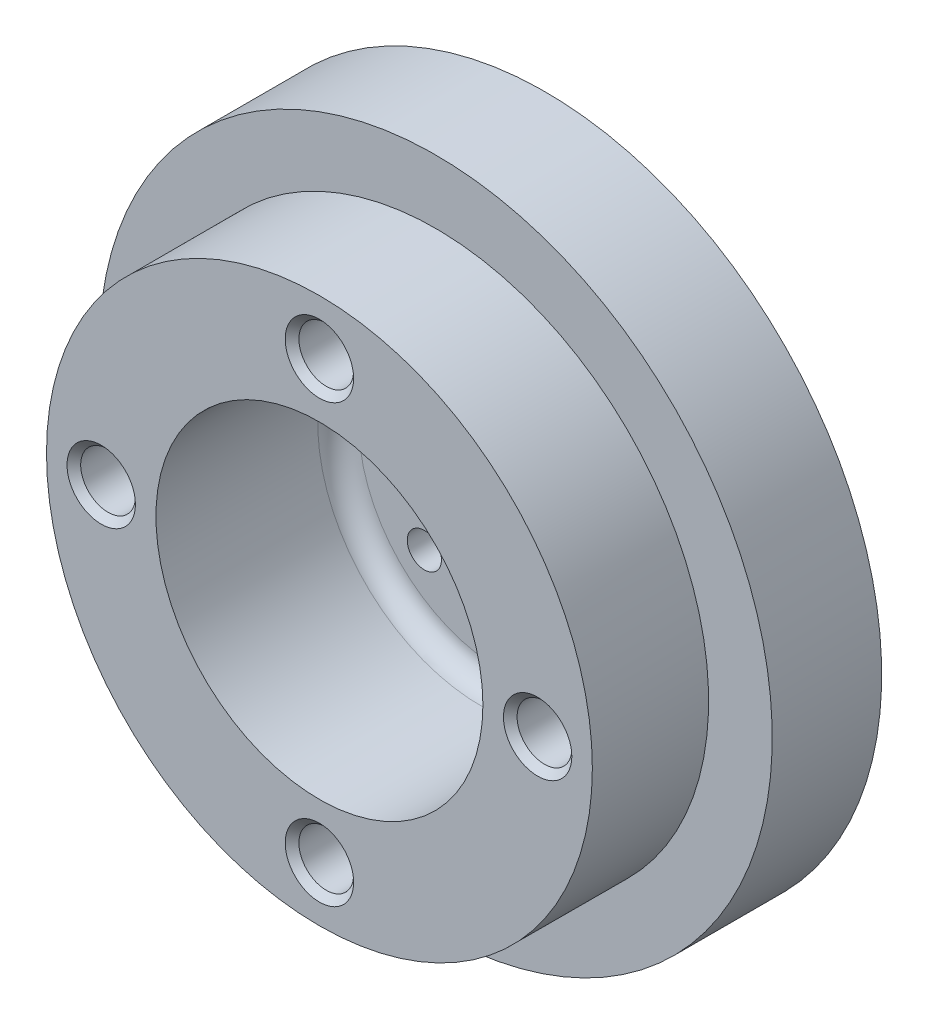
SolidWorks part; units mm, degrees
ref_plane "Front Plane" through (0, 0, 0) normal (0, 0, 1) x (1, 0, 0)
ref_plane "Top Plane" through (0, 0, 0) normal (0, 1, 0) x (1, 0, 0)
ref_plane "Right Plane" through (0, 0, 0) normal (1, 0, 0) x (0, 0, -1)
sketch "Sketch1" plane through (0, 0, 0) normal (0, 0, 1) x (1, 0, 0)
  circle A2 centre (0, 12) radius 4.2
  circle A3 centre (0, 12) radius 4.2
  circle A5 centre (0, 12) radius 19.75
  circle A6 centre (0, 12) radius 19.75
  circle A11 centre (5.6569, 17.6569) radius 1.25
  circle A12 centre (5.6569, 17.6569) radius 1.25
  circle A49 centre (8, 12) radius 1.25
  circle A50 centre (8, 12) radius 1.25
  circle A52 centre (5.6569, 6.3431) radius 1.25
  circle A53 centre (5.6569, 6.3431) radius 1.25
  circle A55 centre (0, 4) radius 1.25
  circle A56 centre (0, 4) radius 1.25
  circle A58 centre (-5.6569, 6.3431) radius 1.25
  circle A59 centre (-5.6569, 6.3431) radius 1.25
  circle A61 centre (-8, 12) radius 1.25
  circle A62 centre (-8, 12) radius 1.25
  circle A64 centre (-5.6569, 17.6569) radius 1.25
  circle A65 centre (-5.6569, 17.6569) radius 1.25
  circle A67 centre (0, 20) radius 1.25
  circle A68 centre (0, 20) radius 1.25
  dimension "D1" = 0.2
  dimension "D2" = 0.25
  dimension "D3" = 0.5
  dimension "D4" = 0.5
  dimension "D5" = 0.5
  dimension "D6" = 0.5
  dimension "D7" = 0.5
  dimension "D8" = 0.5
  dimension "D9" = 0.5
  dimension "D10" = 0.5
extrude "Boss-Extrude1" add sketch "Sketch1" along normal blind 3.175
sketch "Sketch3" plane through (0, 0, 3.175) normal (0, 0, 1) x (1, 0, 0)
  circle A1 centre (0, 12) radius 19.95
  circle A2 centre (0, 12) radius 11.95
  dimension "D2" = 39.9
  dimension "D1" = 8
extrude "Boss-Extrude2" add sketch "Sketch3" along normal offset from surface (13.325 mm away) 0.5
sketch "Sketch4" plane through (0, 0, 16.5) normal (0, 0, 1) x (1, 0, 0)
  line L0 (-19.95, 12) -> (-11.95, 12) construction
  circle A0 centre (-15.95, 12) radius 2
  circle A1 centre (0, 12) radius 19.95 construction
  circle A2 centre (0, 12) radius 11.95 construction
  point P9 (-15.95, 12)
  dimension "D1" = 4
extrude "Cut-Extrude1" cut sketch "Sketch4" against normal through all
pattern_circular "CirPattern1" count 4 over 360 about axis through (0, 12, 0) along (0, 0, 1) of "Cut-Extrude1"
sketch "Sketch5" plane through (0, 0, 0) normal (0, 0, -1) x (-1, 0, 0)
  circle A0 centre (0, 12) radius 19.75 construction
  circle A1 centre (0, 12) radius 19.75
  circle A2 centre (0, 12) radius 24.6 construction
  circle A3 centre (0, 12) radius 24.6
extrude "Boss-Extrude3" add sketch "Sketch5" against normal up to surface (8 mm away)
chamfer "Chamfer1" distance 0.5 angle 45 4 edges at (13.95, 12, 16.5) (0, 25.95, 16.5) (0, -1.95, 16.5) (-13.95, 12, 16.5)
fillet "Fillet1" radius 1.5 1 edges at (11.95, 12, 3.175)
equation "\"D9@Sketch1\"=\"D10@Sketch1\""
equation "\"D8@Sketch1\"=\"D10@Sketch1\""
equation "\"D7@Sketch1\"=\"D10@Sketch1\""
equation "\"D6@Sketch1\"=\"D10@Sketch1\""
equation "\"D5@Sketch1\"=\"D10@Sketch1\""
equation "\"D4@Sketch1\"=\"D10@Sketch1\""
equation "\"D3@Sketch1\"=\"D10@Sketch1\""
